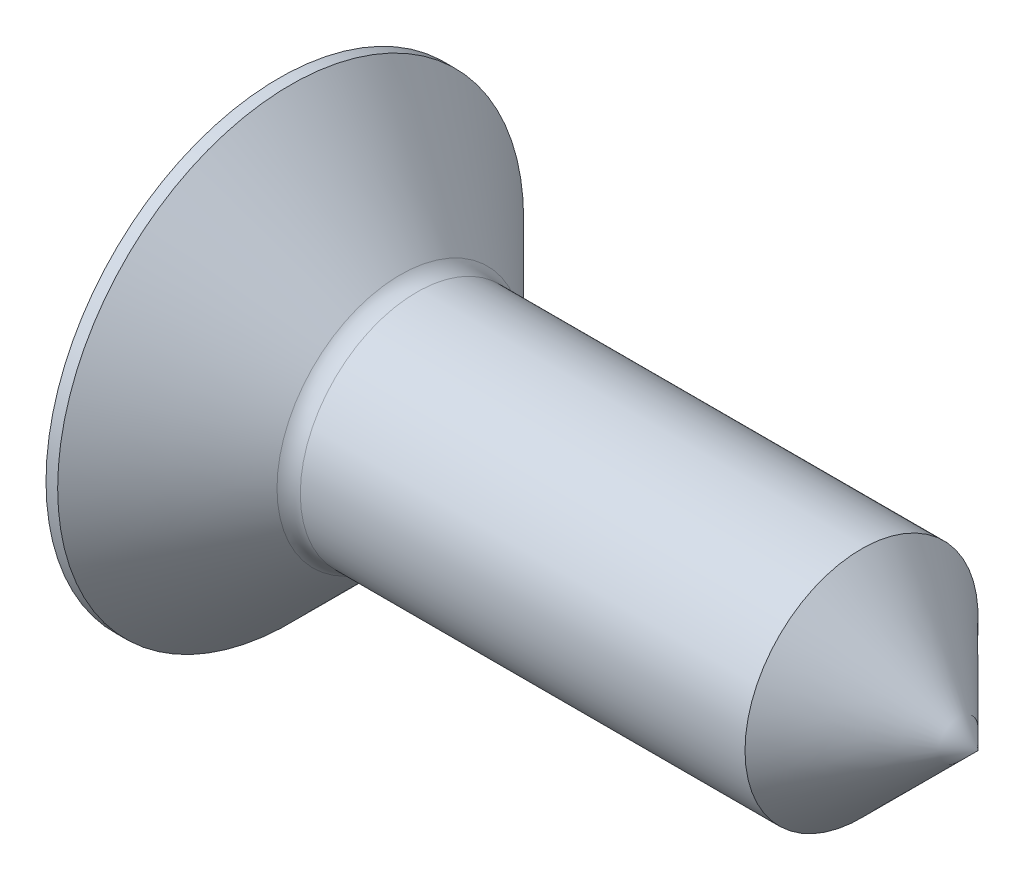
SolidWorks part; units mm, degrees
ref_plane "Front" through (0, 0, 0) normal (0, 0, 1) x (1, 0, 0)
ref_plane "Top" through (0, 0, 0) normal (0, 1, 0) x (1, 0, 0)
ref_plane "Right" through (0, 0, 0) normal (1, 0, 0) x (0, 0, -1)
sketch "Sketch1" plane through (0, 0, 0) normal (0, 1, 0) x (1, 0, 0)
  line L0 (-6.5065, 0) -> (5.6973, 0) construction
  line L1 (2.2, 2) -> (12, 2)
  line L2 (2.2, 2) -> (0.2, 4)
  line L3 (0.2, 4) -> (0, 4)
  line L4 (0, 4) -> (0, 0)
  line L5 (12, 2) -> (12, 0)
  line L6 (12, 0) -> (0, 0)
  dimension "D1" = 45
  dimension "d" = 4
  dimension "dk" = 8
  dimension "k" = 2.2
revolve "Base" add sketch "Sketch1" angle 360 about L0
cosmetic thread "ThreadCosmetic1" [suppressed] parameters "D1"=6, "D2"=3.7
sketch "Sketch3" plane through (0, 0, 0) normal (0, 0, 1) x (1, 0, 0)
  line L0 (4.8835, 0) -> (6.2249, 0) construction
  line L2 (12.1576, 0) -> (12.1576, 20)
  line L3 (12.1576, 20) -> (-8, 20)
  line L4 (-8, 20) -> (12, 0)
  line L5 (12, 0) -> (12.1576, 0)
  line L7 (12, -2) -> (12, 2) construction
  dimension "D1" = 45
  dimension "D2" = 20
  dimension "D3" = 0.1576
revolve "Cut-Revolve1" cut sketch "Sketch3" angle 360 about L0
fillet "Fillet2" radius 0.4 1 edges at (2.2, 0, 2)
ref_plane "Plane1" through (2.45, 0, 0) normal (-1, 0, 0) x (0, 0, 1)
sketch "Sketch2" plane through (0, -0.6808, 0.3068) normal (-1, 0, 0) x (0, 0, 1)
  line L0 (-2.5747, 0.6808) -> (1.9612, 0.6808) construction
  line L1 (-0.3068, 2.9897) -> (-0.3068, -1.628) construction
  line L2 (-0.7868, 1.1608) -> (-2.7068, 1.1608)
  line L3 (0.1732, -1.7192) -> (-0.7868, -1.7192)
  line L4 (0.1732, -1.7192) -> (0.1732, 0.2008)
  line L5 (0.1732, 3.0808) -> (-0.7868, 3.0808)
  line L6 (-0.7868, -1.7192) -> (-0.7868, 0.2008)
  line L7 (2.0932, 1.1608) -> (0.1732, 1.1608)
  line L8 (2.0932, 1.1608) -> (2.0932, 0.2008)
  line L9 (2.0932, 0.2008) -> (0.1732, 0.2008)
  line L10 (-2.7068, 1.1608) -> (-2.7068, 0.2008)
  line L11 (-0.7868, 0.2008) -> (-2.7068, 0.2008)
  line L12 (-0.7868, 1.1608) -> (-0.7868, 3.0808)
  line L13 (0.1732, 1.1608) -> (0.1732, 3.0808)
  point P19 (-0.7868, 1.1608)
  point P24 (0.1732, 1.1608)
  dimension "m" = 4.8
  dimension "D2" = 4.8
  dimension "D1" = 0.96
  dimension "D3" = 0.96
sketch "Sketch4" plane through (2.45, 0, 0) normal (-1, 0, 0) x (0, 0, 1)
  point P0 (0, 0)
loft "Cut-Loft1" cut profiles "Sketch2", "Sketch4"
sketch "Sketch5" plane through (0, 0, 0) normal (0, 0, 1) x (1, 0, 0)
  line L0 (4, 2.2) -> (4.15, 2.2)
  line L1 (4.15, 2.2) -> (4.15, 2)
  line L2 (4.15, 2) -> (4.075, 1.8701)
  line L3 (4, 2) -> (4.075, 1.8701)
  line L4 (4, 2.2) -> (4, 2)
  line L5 (10.7743, 0) -> (0, 0) construction
  line L6 (4, 2) -> (4.15, 2) construction
  line L7 (4.075, 2) -> (4.075, 1.8701) construction
  line L8 (10, 2) -> (2.3657, 2) construction
  point P5 (4.075, 2.2)
  dimension "D1" = 0.2
  dimension "D3" = 36
revolve "Cut-Revolve10" [suppressed] cut sketch "Sketch5" angle 360 about L5
pattern_linear "LPattern10" [suppressed] count 120 spacing 0.3 along (1, 0, 0)
equation "\"D2@Sketch2\" = \"m@Sketch2\""
equation "\"D3@Sketch2\" = \"D1@Sketch2\""
equation "\"D1@Sketch2\" = \"m@Sketch2\" / 5"
equation "\"D1@Plane1\" = \"k@Sketch1\" + 0.25"
equation "\"D2@Sketch5\" =  ( \"d@Sketch1\" - \"D2@ThreadCosmetic1\" )  / 2"
equation "\"D3@Sketch5\" = \"D1@ThreadCosmetic1\" + \"d@Sketch1\" / 2"
equation "\"D3@LPattern10\" =\"D2@Sketch5\"* 2"
equation "\"D1@LPattern10\" = \"D3@Sketch5\" / \"D3@LPattern10\""
